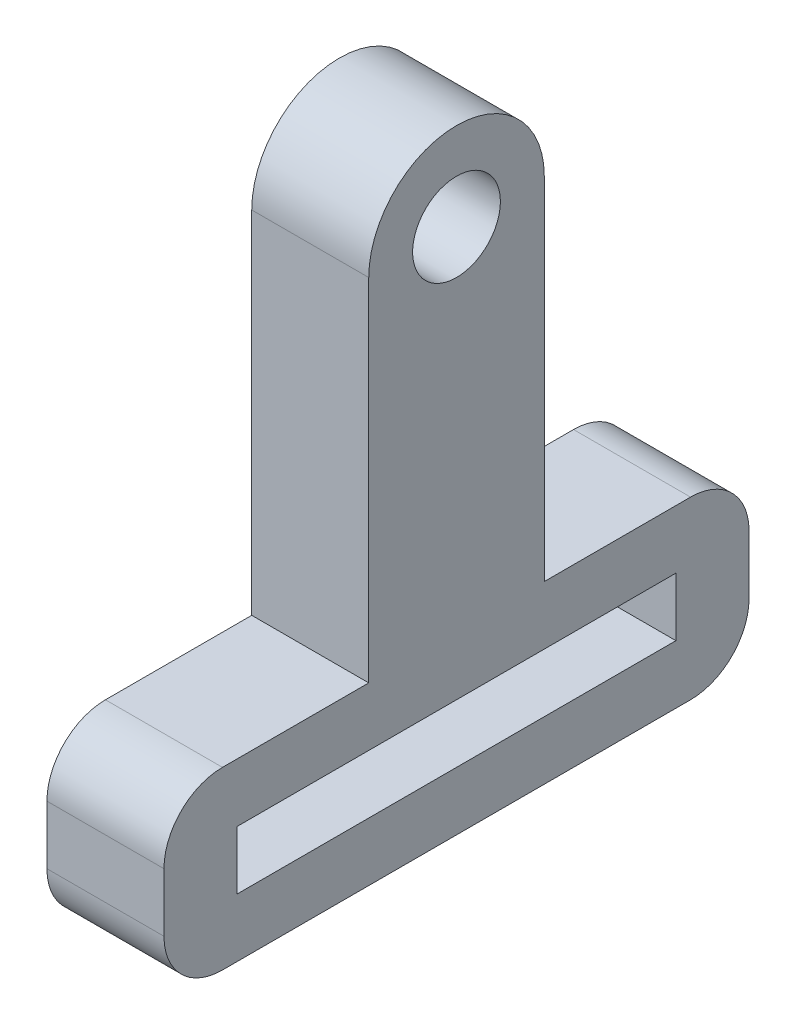
SolidWorks part; units mm, degrees
ref_plane "Alzado" through (0, 0, 0) normal (0, 0, 1) x (1, 0, 0)
ref_plane "Planta" through (0, 0, 0) normal (0, 1, 0) x (1, 0, 0)
ref_plane "Vista lateral" through (0, 0, 0) normal (1, 0, 0) x (0, 0, -1)
sketch "Croquis1" plane through (0, 0, 0) normal (1, 0, 0) x (0, 0, -1)
  line L2 (-10, 1) -> (-10, -1)
  line L3 (-8, -3) -> (8, -3)
  line L4 (10, 1) -> (10, -1)
  line L5 (-10, 3) -> (10, -3) construction
  line L6 (-10, -3) -> (10, 3) construction
  line L7 (-7.5, 1) -> (7.5, 1)
  line L8 (-7.5, 1) -> (-7.5, -1)
  line L9 (-7.5, -1) -> (7.5, -1)
  line L10 (7.5, 1) -> (7.5, -1)
  line L11 (-7.5, 1) -> (7.5, -1) construction
  line L12 (-7.5, -1) -> (7.5, 1) construction
  line L15 (-10, 3) -> (10, 3) construction
  line L27 (-3, 3) -> (-8, 3)
  line L28 (3, 3) -> (8, 3)
  line L35 (0, 3) -> (0, 15) construction
  line L36 (-3, 15) -> (-3, 3)
  line L39 (3, 15) -> (3, 3)
  circle A1 centre (0, 15) radius 1.5
  arc A2 (3, 15) -> (-3, 15) centre (0, 15) ccw
  arc A3 (8, -3) -> (10, -1) centre (8, -1) ccw
  arc A4 (8, 3) -> (10, 1) centre (8, 1) cw
  arc A5 (-10, -1) -> (-8, -3) centre (-8, -1) ccw
  arc A6 (-8, 3) -> (-10, 1) centre (-8, 1) ccw
  point P0 (0, 0)
  point P6 (0, 0)
  dimension "D18" = 6
  dimension "D17" = 3
  dimension "D6" = 2
  dimension "D2" = 20
  dimension "D3" = 2
  dimension "D4" = 15
  dimension "D5" = 6
  dimension "D16" = 12
  dimension "D23" = 2
extrude "Saliente-Extruir1" add sketch "Croquis1" along normal mid plane 4
